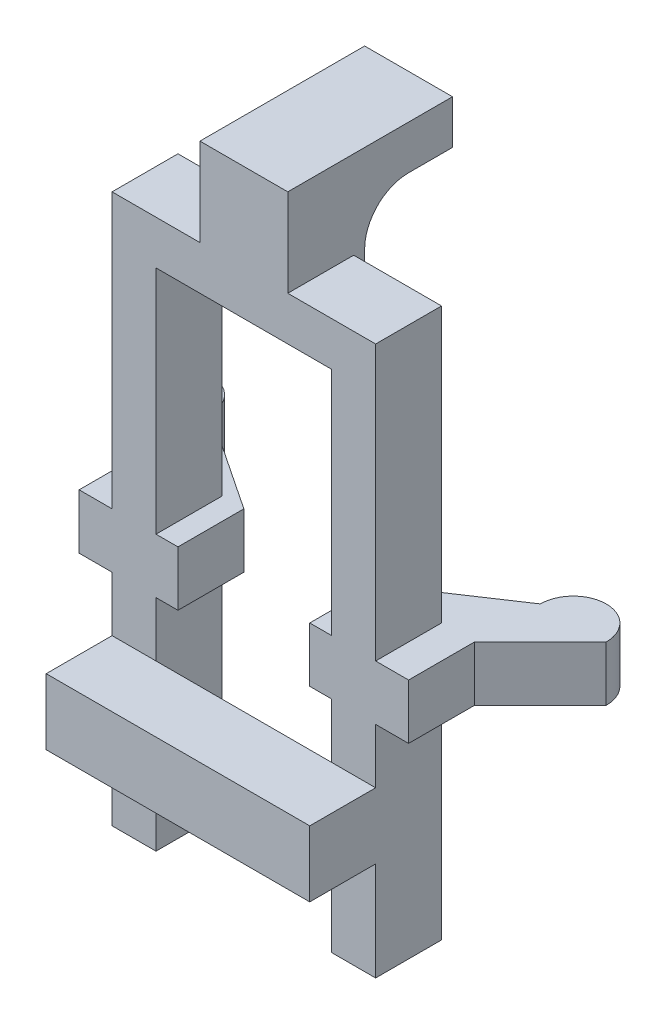
SolidWorks part; units mm, degrees
ref_plane "Front Plane" through (0, 0, 0) normal (0, 0, 1) x (1, 0, 0)
ref_plane "Top Plane" through (0, 0, 0) normal (0, 1, 0) x (1, 0, 0)
ref_plane "Right Plane" through (0, 0, 0) normal (1, 0, 0) x (0, 0, -1)
sketch "Sketch1" plane through (0, 0, 0) normal (0, 0, 1) x (1, 0, 0)
  line L0 (-60, 0) -> (-40, 0)
  line L1 (-40, 0) -> (-40, 230)
  line L2 (-40, 230) -> (40, 230)
  line L3 (40, 230) -> (40, 0)
  line L4 (40, 0) -> (60, 0)
  line L5 (60, 0) -> (60, 250)
  line L6 (60, 250) -> (-60, 250)
  line L7 (-60, 250) -> (-60, 0)
  line L8 (0, 0) -> (0, 72) construction
  point P11 (0, 0)
  point P12 (0, 0)
  point P13 (38.8571, 80)
  point P14 (0, 0)
  dimension "D1" = 20
  dimension "D2" = 20
  dimension "D3" = 120
  dimension "D4" = 250
extrude "Boss-Extrude1" add sketch "Sketch1" along normal blind 30
ref_plane "Plane1" through (0, 100, 0) normal (0, -1, 0) x (-1, 0, 0)
sketch "Sketch4" plane through (0, 100, 0) normal (0, -1, 0) x (-1, 0, 0)
  line L0 (-60, -30) -> (-75, -30)
  line L1 (-75, -30) -> (-75, 0)
  line L2 (-75, 0) -> (-105, 30)
  line L4 (-40, 0) -> (-60, 0) construction
  line L5 (-75, 30) -> (-30, 0)
  line L6 (40, 0) -> (-40, 0) construction
  line L7 (-30, 0) -> (-30, -30)
  line L8 (40, -30) -> (-40, -30) construction
  line L9 (-30, -30) -> (-60, -30)
  line L10 (-40, -30) -> (-40, 0) construction
  arc A0 (-105, 30) -> (-75, 30) centre (-90, 30) cw
  point P9 (-50, 0)
  point P15 (-75, 30)
  dimension "D5" = 15
  dimension "D1" = 15
  dimension "D2" = 30
  dimension "D3" = 40
  dimension "D4" = 30
  dimension "D6" = 10
extrude "Boss-Extrude2" add sketch "Sketch4" against normal blind 25
mirror "Mirror1" about plane through (0, 0, 0) normal (1, 0, 0) of "Boss-Extrude2"
sketch "Sketch5" plane through (-60, 0, 0) normal (-1, 0, 0) x (0, 0, 1)
  line L0 (30, 250) -> (30, 125) construction
  line L1 (30, 75) -> (60, 75)
  line L2 (30, 75) -> (30, 45)
  line L3 (30, 45) -> (60, 45)
  line L4 (60, 75) -> (60, 45)
  line L5 (30, 0) -> (0, 0) construction
  point P8 (60, 119.7737)
  dimension "D1" = 45
  dimension "D2" = 30
extrude "Boss-Extrude8" add sketch "Sketch5" against normal up to surface (120 mm away) up to face at (60, 50, 15)
sketch "Sketch6" plane through (0, 0, 0) normal (1, 0, 0) x (0, 0, -1)
  line L0 (-30, 230) -> (5, 230)
  line L1 (-30, 125) -> (-30, 250) construction
  line L2 (5, 230) -> (5, 250)
  line L3 (-30, 230) -> (-30, 290)
  line L4 (-30, 290) -> (45, 290)
  line L5 (45, 290) -> (45, 270)
  line L6 (45, 270) -> (25, 270)
  line L7 (-30, 250) -> (0, 250) construction
  line L8 (0, 125) -> (0, 250) construction
  arc A0 (5, 250) -> (25, 270) centre (25, 250) cw
  dimension "D1" = 20
  dimension "D2" = 35
  dimension "D3" = 20
  dimension "D4" = 40
  dimension "D5" = 20
  dimension "D6" = 45
extrude "Boss-Extrude9" add sketch "Sketch6" along normal mid plane 40
